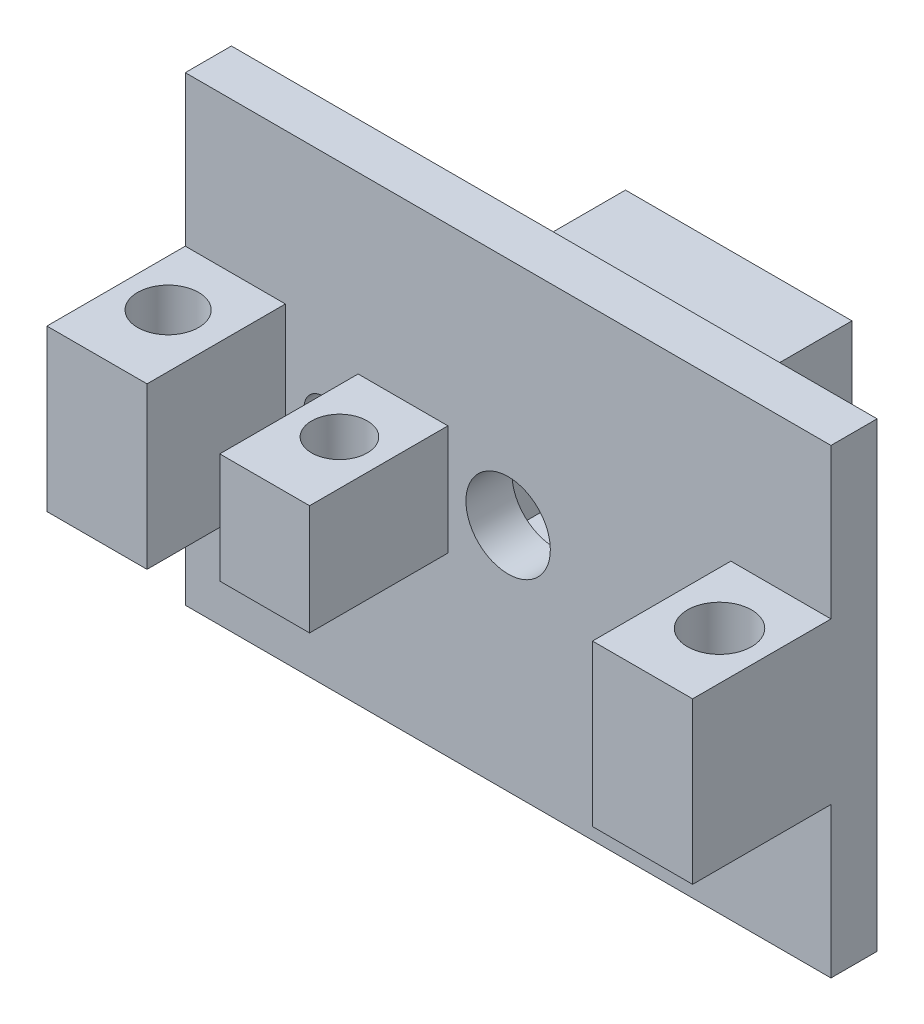
SolidWorks part; units mm, degrees
ref_plane "Plan de face" through (0, 0, 0) normal (0, 0, 1) x (1, 0, 0)
ref_plane "Plan de dessus" through (0, 0, 0) normal (0, 1, 0) x (1, 0, 0)
ref_plane "Plan de droite" through (0, 0, 0) normal (1, 0, 0) x (0, 0, -1)
sketch "Esquisse1" plane through (0, 0, 0) normal (0, 0, 1) x (1, 0, 0)
  line L0 (0, 28.3337) -> (0, 11.1085) construction
  line L1 (-70, -50) -> (70, -50)
  line L2 (-70, -50) -> (-70, 50)
  line L3 (-70, 50) -> (70, 50)
  line L4 (70, -50) -> (70, 50)
  line L5 (-70, -50) -> (70, 50) construction
  line L6 (-70, 50) -> (70, -50) construction
  circle A0 centre (-40, 0) radius 4.25
  circle A1 centre (40, 0) radius 4.25
  circle A2 centre (0, 0) radius 9.1516
  point P0 (0, 0)
  dimension "D3" = 8.5
  dimension "D5" = 30
  dimension "D1" = 140
  dimension "D2" = 100
  dimension "D4" = 50
extrude "Boss.-Extru.1" add sketch "Esquisse1" along normal blind 10
sketch "Esquisse2" plane through (0, 0, 0) normal (0, 0, -1) x (-1, 0, 0)
  line L0 (-24.5535, 25.6723) -> (24.5535, 25.6723)
  line L1 (-19.5535, -20.6723) -> (19.5535, -20.6723)
  line L2 (-19.5535, -20.6723) -> (-19.5535, 20.6723)
  line L3 (-19.5535, 20.6723) -> (19.5535, 20.6723)
  line L4 (19.5535, -20.6723) -> (19.5535, 20.6723)
  line L5 (-19.5535, -20.6723) -> (19.5535, 20.6723) construction
  line L6 (-19.5535, 20.6723) -> (19.5535, -20.6723) construction
  line L7 (24.5535, -25.6723) -> (24.5535, 25.6723)
  line L8 (-24.5535, -25.6723) -> (24.5535, -25.6723)
  line L9 (-24.5535, -25.6723) -> (-24.5535, 25.6723)
  point P0 (0, 0)
  dimension "D1" = 5
extrude "Boss.-Extru.2" add sketch "Esquisse2" along normal blind 40
sketch "Esquisse3" plane through (0, 0, 10) normal (0, 0, 1) x (1, 0, 0)
  line L0 (0, 0) -> (0, 21.9427) construction
  line L1 (-70, 50) -> (-70, -50) construction
  line L2 (-48.2904, -17.4173) -> (-70, -17.4173)
  line L3 (-48.2904, -17.4173) -> (-48.2904, 17.4173)
  line L4 (-48.2904, 17.4173) -> (-70, 17.4173)
  line L5 (-70, -17.4173) -> (-70, 17.4173)
  line L6 (-48.2904, -17.4173) -> (-70, 17.4173) construction
  line L7 (-48.2904, 17.4173) -> (-70, -17.4173) construction
  line L8 (48.2904, 17.4173) -> (70, 17.4173)
  line L9 (70, -17.4173) -> (70, 17.4173)
  line L10 (48.2904, -17.4173) -> (70, -17.4173)
  line L11 (48.2904, -17.4173) -> (48.2904, 17.4173)
  line L12 (48.2904, 17.4173) -> (70, -17.4173) construction
  line L13 (48.2904, -17.4173) -> (70, 17.4173) construction
  line L15 (-32.5193, -11.7343) -> (-13.0498, -11.7343)
  line L16 (-32.5193, -11.7343) -> (-32.5193, 12.1553)
  line L17 (-32.5193, 12.1553) -> (-13.0498, 12.1553)
  line L18 (-13.0498, -11.7343) -> (-13.0498, 12.1553)
  line L19 (-32.5193, -11.7343) -> (-13.0498, 12.1553) construction
  line L20 (-32.5193, 12.1553) -> (-13.0498, -11.7343) construction
  point P3 (-59.1452, 0)
  point P14 (59.1452, 0)
  point P15 (-22.7846, 0.2105)
extrude "Boss.-Extru.3" add sketch "Esquisse3" along normal blind 30
sketch "Esquisse4" plane through (0, 17.4173, 0) normal (0, 1, 0) x (1, 0, 0)
  circle A0 centre (-59.8819, -23.837) radius 6.6092
  circle A1 centre (-22.732, -23.837) radius 6.0319
  circle A2 centre (59.6714, -23.837) radius 6.9379
extrude "Enlèv. mat.-Extru.1" cut sketch "Esquisse4" against normal through all
